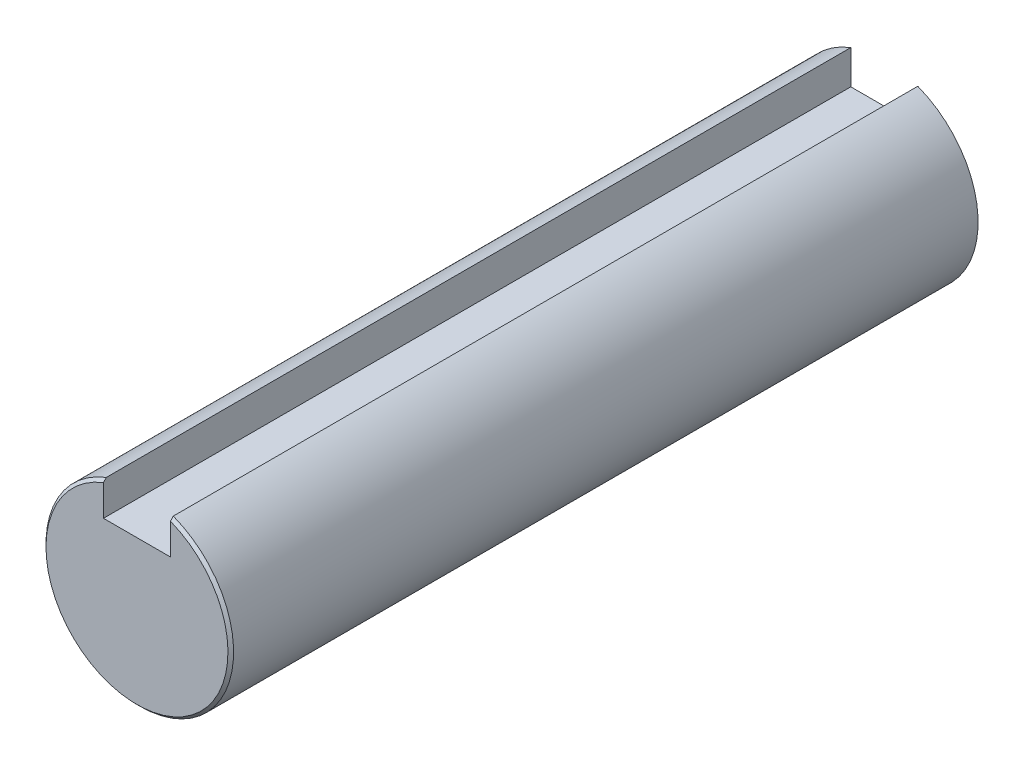
SolidWorks part; units mm, degrees
material "Cast Carbon Steel"
ref_plane "Front Plane" through (0, 0, 0) normal (0, 0, 1) x (1, 0, 0)
ref_plane "Top Plane" through (0, 0, 0) normal (0, 1, 0) x (1, 0, 0)
ref_plane "Right Plane" through (0, 0, 0) normal (1, 0, 0) x (0, 0, -1)
sketch "Sketch1" plane through (0, 0, 0) normal (1, 0, 0) x (0, 0, -1)
  line L0 (0, 0) -> (0, 7) construction
  line L1 (-100, 7) -> (100, 7)
  line L2 (-100, 7) -> (-100, -7)
  line L3 (-100, -7) -> (100, -7)
  line L4 (100, 7) -> (100, -7)
  line L5 (-100, 7) -> (100, -7) construction
  line L6 (-100, -7) -> (100, 7) construction
  line L7 (0, 0) -> (0, -7) construction
  point P0 (0, 0)
  point P8 (-83.9, 7)
  point P10 (83.9, 7)
  point P11 (-100, 0)
  dimension "Diameter" = 14
  dimension "Length" = 200
  dimension "D1" = 16.1
  dimension "D2" = 16.1
  dimension "Keyway Length" = 200
sketch "Sketch2" plane through (0, 0, 0) normal (0, 0, 1) x (1, 0, 0)
  line L0 (0, 0) -> (0, 7) construction
  line L2 (2.5, 4) -> (-2.5, 4) construction
  line L3 (2.5, 4) -> (2.5, 7) construction
  line L4 (2.5, 7) -> (-2.5, 7) construction
  line L5 (-2.5, 4) -> (-2.5, 7) construction
  line L6 (2.5, 4) -> (-2.5, 7) construction
  line L7 (2.5, 7) -> (-2.5, 4) construction
  circle A0 centre (0, 0) radius 7 construction
  point P3 (0, 5.5)
  dimension "Keyway Width" = 5
  dimension "Keyway Depth" = 3
sketch "Sketch3" plane through (0, 0, 0) normal (0, 0, 1) x (1, 0, 0)
  line L1 (-2.5, 4) -> (-2.5, 7) construction
  line L2 (2.5, 4) -> (-2.5, 4) construction
  line L3 (2.5, 4) -> (2.5, 7) construction
  line L5 (-2.5, 4) -> (-2.5, 6.5383)
  line L6 (2.5, 4) -> (-2.5, 4)
  line L7 (2.5, 4) -> (2.5, 6.5383)
  arc A1 (-2.5, 6.5383) -> (2.5, 6.5383) centre (0, 0) ccw
  circle A2 centre (0, 0) radius 7 construction
extrude "Boss-Extrude1" add sketch "Sketch3" along normal up to vertex (100 mm away) and the other way up to vertex (100 mm away) up to point (0, 7, 100) other way up to point (0, 7, -100)
chamfer "Chamfer1" distance 0.21 angle 45 2 edges at (0, -7, -100) (0, -7, 100)
sketch "Sketch4" plane through (0, 0, 0) normal (0, 1, 0) x (1, 0, 0)
  line L0 (2.5, 100) -> (-2.5, 100) construction
  line L1 (-29.9146, 100) -> (75.0166, 100)
  line L2 (-29.9146, 100) -> (-29.9146, -44.2275)
  line L3 (-29.9146, -44.2275) -> (75.0166, -44.2275)
  line L4 (75.0166, 100) -> (75.0166, -44.2275)
  dimension "D1" = 55.5625
extrude "Cut-Extrude1" cut sketch "Sketch4" against normal through all both and the other way through all
sketch "Sketch5" plane through (0, 0, 0) normal (1, 0, 0) x (0, 0, -1)
  line L0 (-100, -0.2385) -> (-44.2275, -0.2308) construction
  line L1 (-101.1325, -10.103) -> (-43.095, -10.103)
  line L2 (-101.1325, -10.103) -> (-101.1325, 9.6417)
  line L3 (-101.1325, 9.6417) -> (-43.095, 9.6417)
  line L4 (-43.095, -10.103) -> (-43.095, 9.6417)
  line L5 (-100, 6.313) -> (-100, -6.79) construction
  line L6 (-44.2275, -7) -> (-44.2275, 6.5383) construction
  line L7 (-72.1137, -0.2347) -> (-72.1137, -10.103) construction
  point P12 (-43.095, -0.2307)
  dimension "D1" = 58.0375
ref_plane "Plane1" through (0, 0, 101.1325) normal (0, 0, 1) x (1, 0, 0)
ref_plane "Plane2" through (0, 0, 43.095) normal (0, 0, -1) x (-1, 0, 0)
sketch "Sketch6" plane through (0, 0, 101.1325) normal (0, 0, 1) x (1, 0, 0)
  circle A0 centre (0, 0) radius 6.45
  circle A1 centre (0, 0) radius 7
  arc A2 (-2.5, 6.5383) -> (2.5, 6.5383) centre (0, 0) ccw construction
  dimension "D1" = 12.9
ref_plane "Plane3" through (0, 0, 72.1137) normal (0, 0, 1) x (1, 0, 0)
equation "\"D2@Sketch1\"=1.15*\"Diameter@Sketch1\""
equation "\"D1@Sketch1\"=\"D2@Sketch1\""
equation "\"D1@Chamfer1\"=\"Diameter@Sketch1\"*.015"
